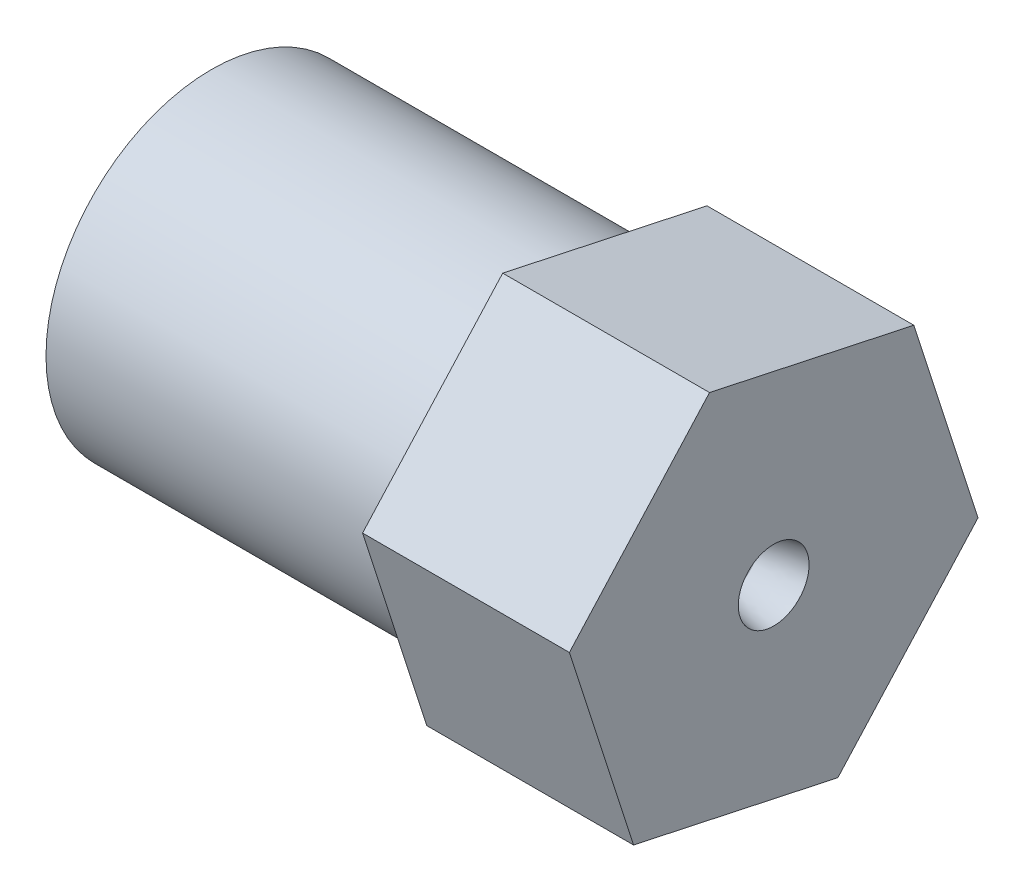
SolidWorks part; units mm, degrees
ref_plane "Front Plane" through (0, 0, 0) normal (0, 0, 1) x (1, 0, 0)
ref_plane "Top Plane" through (0, 0, 0) normal (0, 1, 0) x (1, 0, 0)
ref_plane "Right Plane" through (0, 0, 0) normal (1, 0, 0) x (0, 0, -1)
sketch "Sketch1" plane through (0, 0, 0) normal (0, 0, 1) x (1, 0, 0)
  line L0 (0, 0) -> (2.7749, 0) construction
  line L1 (0.2052, 1.5362) -> (2.7749, 2.4715) construction
  line L2 (-1.591, 2.159) -> (-2.947, 3.5151)
  line L3 (-31.75, 4.445) -> (-31.75, 10.16) construction
  line L4 (-5.1921, 4.445) -> (-31.75, 4.445) construction
  line L5 (-31.75, 10.16) -> (-9.9251, 10.16)
  line L6 (2.7749, 10.16) -> (2.7749, 2.1737)
  line L7 (2.7749, 2.1737) -> (13.0713, 3.6208) construction
  line L8 (-9.9251, 10.16) -> (2.7749, 10.16)
  line L9 (-5.1921, 4.445) -> (-13.462, 4.445)
  line L10 (-19.939, 5.461) -> (-19.939, 6.8199)
  line L11 (-20.066, 6.9469) -> (-24.892, 6.9469)
  line L12 (-24.892, 6.9469) -> (-24.892, 7.8994)
  line L13 (-25.019, 8.0264) -> (-31.115, 8.0264)
  line L14 (-31.75, 10.16) -> (-31.75, 8.6614)
  line L15 (0, 0) -> (-31.75, 0) construction
  line L16 (-13.462, 4.445) -> (-13.462, 4.699)
  line L17 (-13.589, 4.826) -> (-19.304, 4.826)
  arc A0 (-1.591, 2.159) -> (0, 1.5) centre (0, 3.75) ccw
  arc A1 (0, 1.5) -> (0.2052, 1.5362) centre (0, 2.1) ccw
  arc A2 (-2.947, 3.5151) -> (-5.1921, 4.445) centre (-5.1921, 1.27) ccw
  arc A3 (-31.115, 8.0264) -> (-31.75, 8.6614) centre (-31.115, 8.6614) cw
  arc A4 (-19.304, 4.826) -> (-19.939, 5.461) centre (-19.304, 5.461) cw
  arc A5 (-13.462, 4.699) -> (-13.589, 4.826) centre (-13.589, 4.699) ccw
  arc A6 (-19.939, 6.8199) -> (-20.066, 6.9469) centre (-20.066, 6.8199) ccw
  arc A7 (-24.892, 7.8994) -> (-25.019, 8.0264) centre (-25.019, 7.8994) ccw
  parabola Q0 (2.7749, 2.1737) -> (0.2052, 1.5362) focus (2.3234, -4.2834) apex (0.2052, 1.5362)
  point P30 (-31.75, 8.0264)
  point P39 (-24.892, 8.0264)
  dimension "D3" = 2.25
  dimension "D4" = 0.6
  dimension "D11" = 3.175
  dimension "D12" = 8
  dimension "D14" = 6.9469
  dimension "D20" = 0.635
  dimension "D21" = 0.127
  dimension "D2" = 2.7749
  dimension "D5" = 2.1737
  dimension "D6" = 20
  dimension "D7" = 45
  dimension "D8" = 8.0264
  dimension "D9" = 31.75
  dimension "D10" = 10.16
  dimension "D13" = 12.7
  dimension "D15" = 4.445
  dimension "D16" = 6.858
  dimension "D17" = 11.811
  dimension "D18" = 18.288
  dimension "D19" = 4.826
  dimension "D22" = 1.5
revolve "Revolve1" add sketch "Sketch1" angle 360 about L0
sketch "Sketch4" plane through (2.7749, 0, 0) normal (1, 0, 0) x (0, 0, -1)
  line L1 (3.9404, -12.2116) -> (12.5458, -2.6933)
  line L2 (12.5458, -2.6933) -> (8.6054, 9.5183)
  line L3 (8.6054, 9.5183) -> (-3.9404, 12.2116)
  line L4 (-3.9404, 12.2116) -> (-12.5458, 2.6933)
  line L5 (-12.5458, 2.6933) -> (-8.6054, -9.5183)
  line L6 (-8.6054, -9.5183) -> (3.9404, -12.2116)
  circle A0 centre (0, 0) radius 10.16
  circle A1 centre (0, 0) radius 10.16 construction
  circle A2 centre (0, 0) radius 11.1125 construction
  circle M1 centre (0, 0) radius 10.16
  dimension "D1" = 22.225
extrude "Boss-Extrude1" add sketch "Sketch4" against normal blind 12.7 contours L4 L5 M1 | L3 L4 M1 | L2 L3 M1 | L1 L2 M1 | L6 L1 M1 | L5 L6 M1
fillet "Fillet1" radius 0.635 1 edges at (-9.9251, 0, -10.16)
equation "\"D3@Sketch1\" = 1.5 * \"D22@Sketch1\""
equation "\"D4@Sketch1\"  = .4 * \"D22@Sketch1\""
equation "\"D5@Sketch1\"=\"D22@Sketch1\" * ( \"er\") ^ .5"
equation "\"er\"= 2.1"
